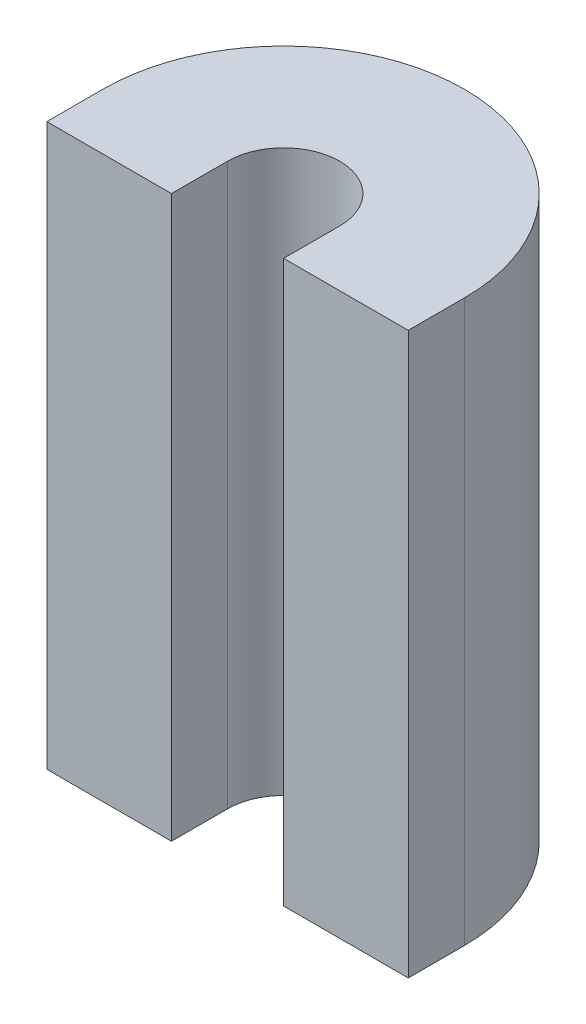
SolidWorks part; units mm, degrees
ref_plane "Front Plane" through (0, 0, 0) normal (0, 0, 1) x (1, 0, 0)
ref_plane "Top Plane" through (0, 0, 0) normal (0, 1, 0) x (1, 0, 0)
ref_plane "Right Plane" through (0, 0, 0) normal (1, 0, 0) x (0, 0, -1)
sketch "Sketch3" plane through (0, 0, 0) normal (0, 1, 0) x (1, 0, 0)
  line L0 (-1.8, -100.4567) -> (-1.8, 4935.9097) construction
  line L1 (1.8, -100.5156) -> (1.8, 4935.8508) construction
  line L2 (-1000, 0) -> (49000, 0) construction
  line L3 (-1.8, 0) -> (-5.8, 0)
  line L4 (-5.8, 0) -> (-5.8, 1.8)
  line L5 (1.8, 1.8) -> (1.8, 0)
  line L6 (-1.8, 1.8) -> (-1.8, 0)
  line L7 (0, -998.2) -> (0, 49001.8) construction
  line L8 (5.8, 0) -> (5.8, 1.8)
  line L9 (1.8, 0) -> (5.8, 0)
  arc A0 (5.8, 1.8) -> (0, 7.6) centre (0, 1.8) ccw
  arc A1 (-1.8, 1.8) -> (0, 3.6) centre (0, 1.8) cw
  arc A2 (-5.8, 1.8) -> (0, 7.6) centre (0, 1.8) cw
  arc A3 (1.8, 1.8) -> (0, 3.6) centre (0, 1.8) ccw
  dimension "D1" = 1.8
  dimension "D2" = 1.8
  dimension "D3" = 1.8
  dimension "D6" = 4
extrude "Boss-Extrude1" add sketch "Sketch3" along normal blind 18
